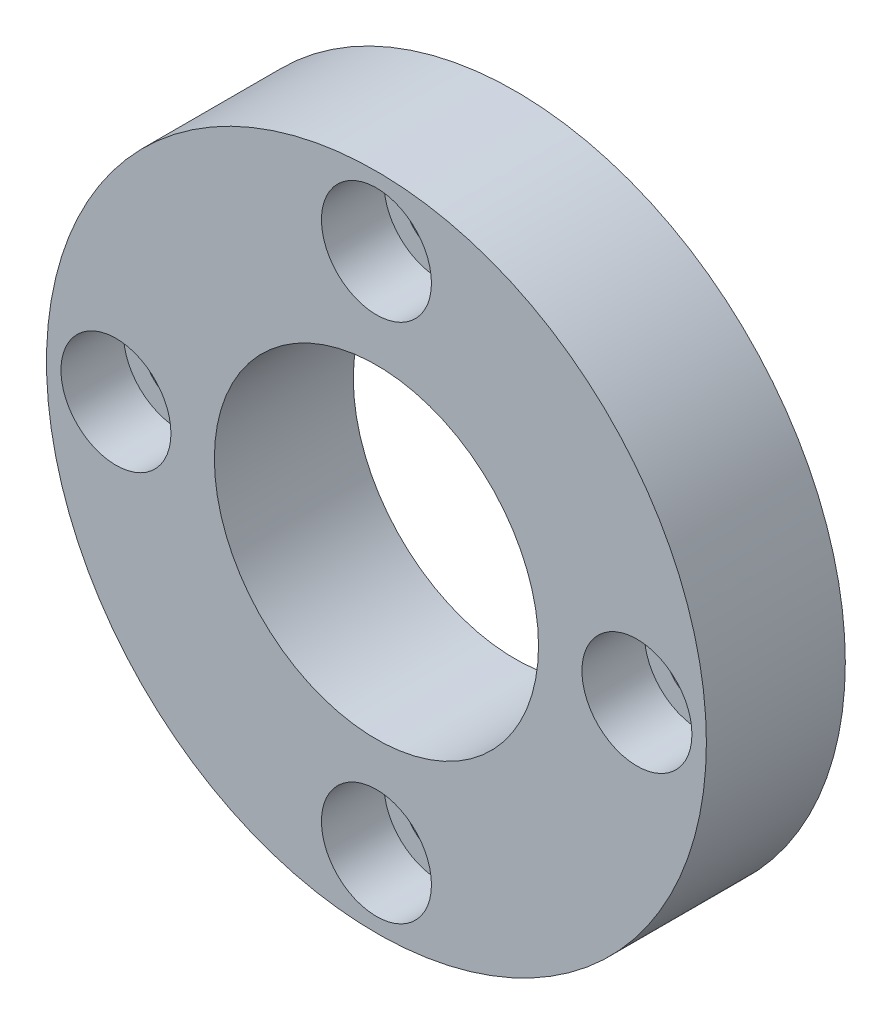
SolidWorks part; units mm, degrees
ref_plane "前视基准面" through (0, 0, 0) normal (0, 0, 1) x (1, 0, 0)
ref_plane "上视基准面" through (0, 0, 0) normal (0, 1, 0) x (1, 0, 0)
ref_plane "右视基准面" through (0, 0, 0) normal (1, 0, 0) x (0, 0, -1)
sketch "草图1" plane through (0, 0, 0) normal (0, 0, 1) x (1, 0, 0)
  circle A0 centre (0, 0) radius 28.5
  circle A1 centre (0, 0) radius 14
  circle A2 centre (0, 0) radius 22.5 construction
  circle A3 centre (0, 22.5) radius 3
  circle A4 centre (22.5, 0) radius 3
  circle A5 centre (0, -22.5) radius 3
  circle A6 centre (-22.5, 0) radius 3
  point P16 (0, 0)
  dimension "D1" = 4
extrude "凸台-拉伸1" add sketch "草图1" along normal blind 12
sketch "草图2" plane through (0, 0, 12) normal (0, 0, 1) x (1, 0, 0)
  circle A0 centre (0, 0) radius 22.5 construction
  circle A1 centre (0, 22.5) radius 4.75
  circle A2 centre (22.5, 0) radius 4.75
  circle A3 centre (0, -22.5) radius 4.75
  circle A4 centre (-22.5, 0) radius 4.75
  point P15 (0, 0)
  dimension "D1" = 4
extrude "切除-拉伸1" cut sketch "草图2" against normal blind 5.4
